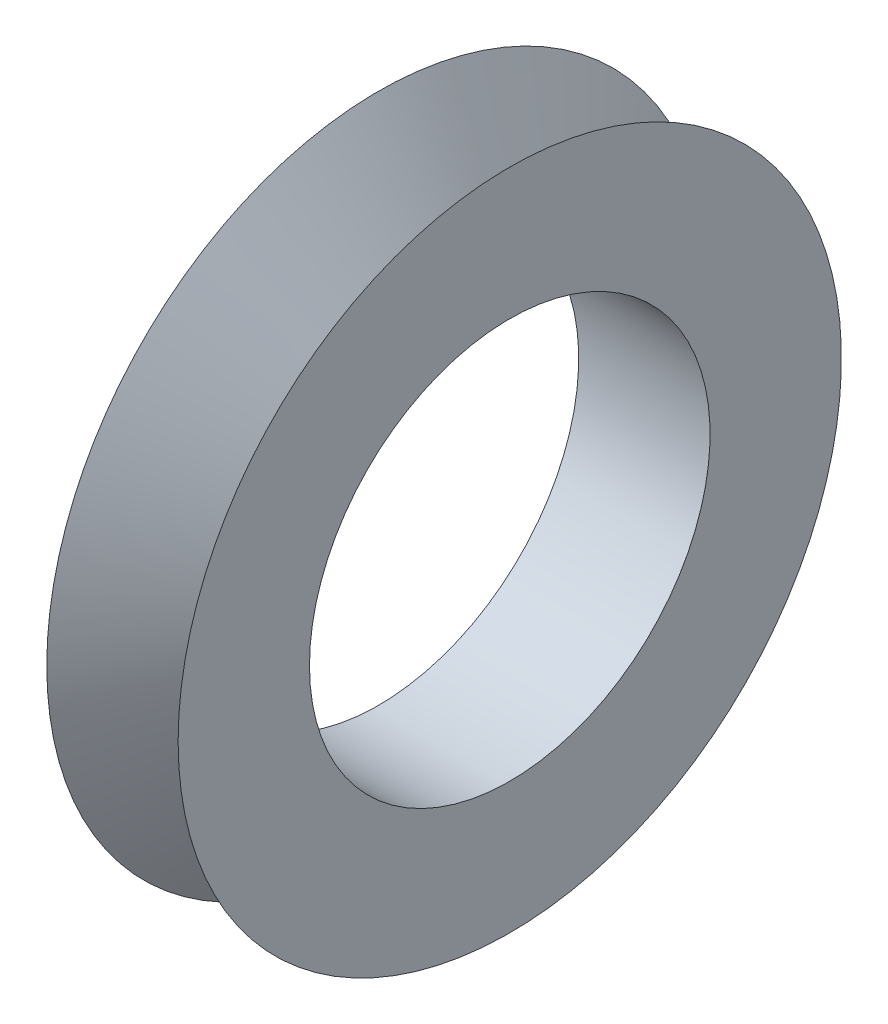
SolidWorks part; units mm, degrees
ref_plane "Front Plane" through (0, 0, 0) normal (0, 0, 1) x (1, 0, 0)
ref_plane "Top Plane" through (0, 0, 0) normal (0, 1, 0) x (1, 0, 0)
ref_plane "Right Plane" through (0, 0, 0) normal (1, 0, 0) x (0, 0, -1)
ref_axis "Axis1" through (-6.9241, 0, 0) along (1, 0, 0)
sketch "Sketch5" plane through (0, 0, 0) normal (0, 0, 1) x (1, 0, 0)
  line L0 (0, 0) -> (0, 6.1) construction
  line L1 (-2, 6.1) -> (2, 6.1)
  line L2 (-2, 6.1) -> (-2, 10.1)
  line L3 (-2, 10.1) -> (0, 7.1)
  line L4 (2, 6.1) -> (2, 10.1)
  line L5 (2, 10.1) -> (0, 7.1)
  point P6 (0, 6.1)
  dimension "D1" = 6.1
  dimension "D2" = 4
  dimension "D3" = 4
  dimension "D4" = 3
revolve "Revolve4" add sketch "Sketch5" angle 360 about axis through (-6.9241, 0, 0) along (1, 0, 0)
